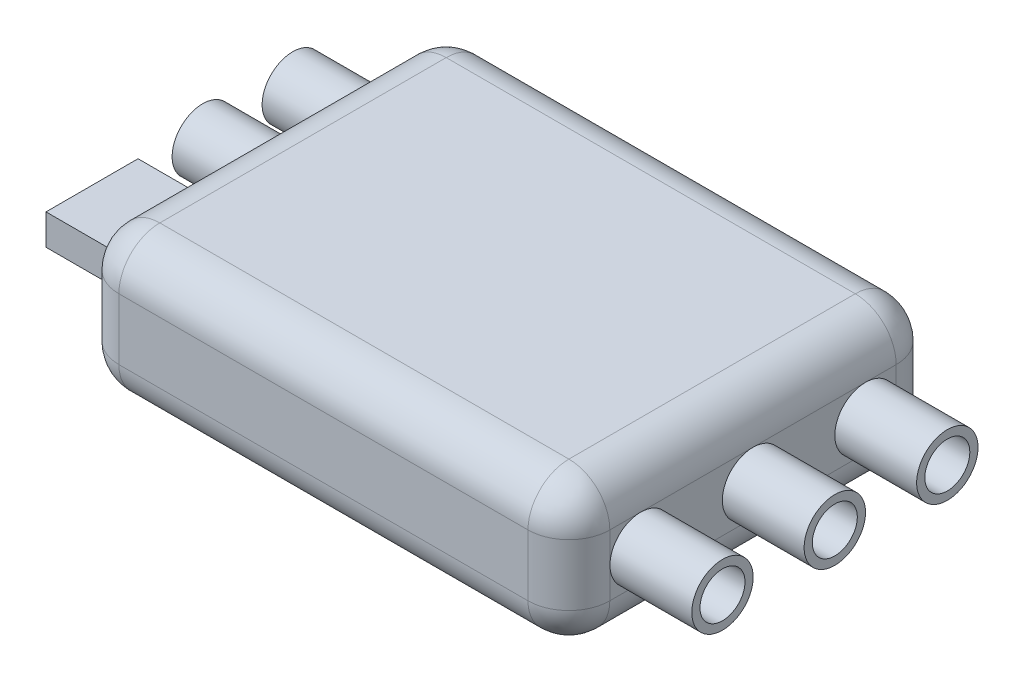
SolidWorks part; units mm, degrees
ref_plane "Front Plane" through (0, 0, 0) normal (0, 0, 1) x (1, 0, 0)
ref_plane "Top Plane" through (0, 0, 0) normal (0, 1, 0) x (1, 0, 0)
ref_plane "Right Plane" through (0, 0, 0) normal (1, 0, 0) x (0, 0, -1)
sketch "Sketch1" plane through (0, 0, 0) normal (0, 1, 0) x (1, 0, 0)
  line L1 (-10, -9) -> (10, -9)
  line L2 (-12, -7) -> (-12, 7)
  line L3 (-10, 9) -> (10, 9)
  line L4 (12, -7) -> (12, 7)
  line L5 (-12, -9) -> (12, 9) construction
  line L6 (-12, 9) -> (12, -9) construction
  arc A0 (10, -9) -> (12, -7) centre (10, -7) ccw
  arc A1 (-12, 7) -> (-10, 9) centre (-10, 7) cw
  arc A2 (-10, -9) -> (-12, -7) centre (-10, -7) cw
  arc A3 (10, 9) -> (12, 7) centre (10, 7) cw
  point P0 (0, 0)
  dimension "D3" = 2
  dimension "D1" = 24
  dimension "D2" = 18
extrude "Boss-Extrude1" add sketch "Sketch1" along normal blind 7
fillet "Fillet1" radius 2 16 edges at (12, 0, 0) (11.4142, 0, -8.4142) (0, 0, -9) (-11.4142, 0, -8.4142) (-12, 0, 0) (-11.4142, 0, 8.4142) (0, 0, 9) (11.4142, 0, 8.4142) (0, 7, 9) (-11.4142, 7, 8.4142) (-12, 7, 0) (-11.4142, 7, -8.4142) (0, 7, -9) (11.4142, 7, -8.4142) (12, 7, 0) (11.4142, 7, 8.4142)
sketch "Sketch2" plane through (12, 0, 0) normal (1, 0, 0) x (0, 0, -1)
  line L0 (-7, 3.5) -> (7, 3.5) construction
  line L1 (-7, 5) -> (-7, 2) construction
  line L2 (7, 5) -> (7, 2) construction
  circle A0 centre (0, 3.5) radius 1.1
  circle A1 centre (0, 3.5) radius 1.5
  circle A2 centre (5.5, 3.5) radius 1.5
  circle A3 centre (5.5, 3.5) radius 1.1
  circle A4 centre (-5.492, 3.5) radius 1.5
  circle A5 centre (-5.492, 3.5) radius 1.1
  dimension "D1" = 3
  dimension "D2" = 0.4
extrude "Boss-Extrude2" add sketch "Sketch2" along normal blind 4
sketch "Sketch3" plane through (-12, 0, 0) normal (-1, 0, 0) x (0, 0, 1)
  line L0 (-7, 3.5) -> (7, 3.5) construction
  line L1 (-7, 5) -> (-7, 2) construction
  line L2 (7, 5) -> (7, 2) construction
  line L4 (2.0648, 2.75) -> (6.5648, 2.75)
  line L5 (2.0648, 2.75) -> (2.0648, 4.25)
  line L6 (2.0648, 4.25) -> (6.5648, 4.25)
  line L7 (6.5648, 2.75) -> (6.5648, 4.25)
  line L8 (2.0648, 2.75) -> (6.5648, 4.25) construction
  line L9 (2.0648, 4.25) -> (6.5648, 2.75) construction
  circle A0 centre (-5.5, 3.5) radius 1.5
  circle A1 centre (-1.1, 3.5) radius 1.5
  circle A2 centre (-5.5, 3.5) radius 1.1
  circle A3 centre (-1.1, 3.5) radius 1.1
  point P6 (4.3148, 3.5)
  dimension "D3" = 3
  dimension "D4" = 0.4
  dimension "D1" = 4.5
  dimension "D2" = 1.5
  dimension "D5" = 4.4
extrude "Boss-Extrude3" add sketch "Sketch3" along normal blind 4
